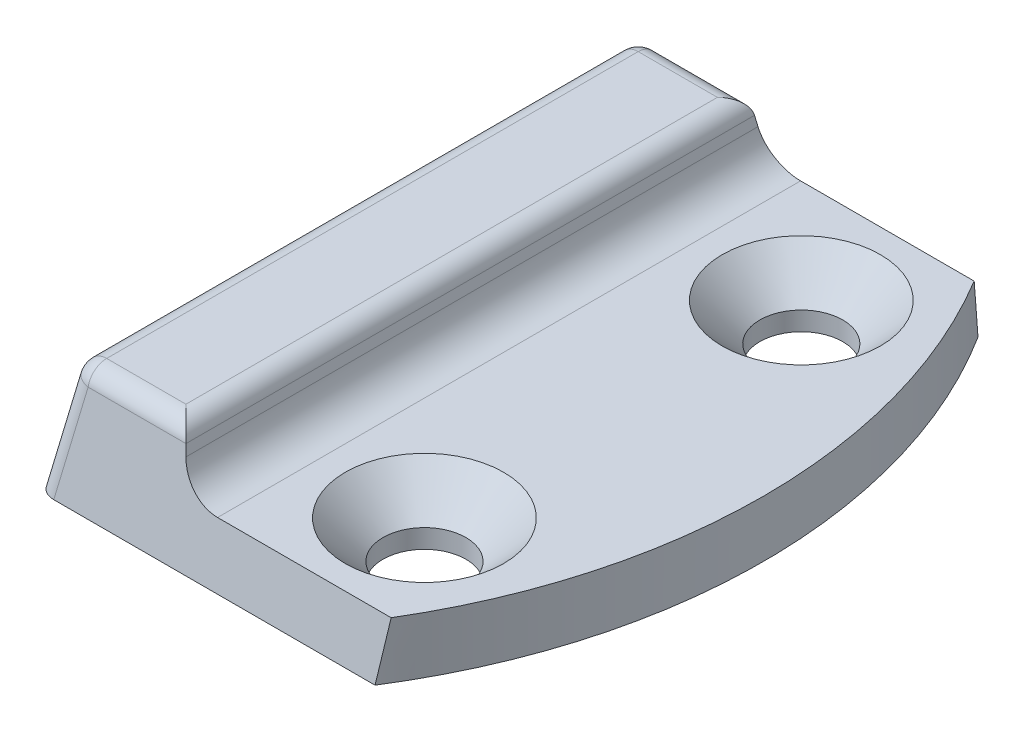
SolidWorks part; units mm, degrees
ref_plane "Спереди" through (0, 0, 0) normal (0, 0, 1) x (1, 0, 0)
ref_plane "Сверху" through (0, 0, 0) normal (0, 1, 0) x (1, 0, 0)
ref_plane "Справа" through (0, 0, 0) normal (1, 0, 0) x (0, 0, -1)
sketch "Эскиз1" plane through (0, 0, 0) normal (0, 1, 0) x (1, 0, 0)
  line L0 (0, 33.2845) -> (0, -21.3972) construction
  line L1 (0, 0) -> (27.1923, 0) construction
  line L3 (3.671, 8) -> (7.671, 8)
  line L4 (3.671, 8) -> (3.671, -8)
  line L5 (3.671, -8) -> (7.671, -8)
  line L6 (7.671, 8) -> (7.671, -8)
  line L7 (3.671, 8) -> (7.671, -8) construction
  line L8 (3.671, -8) -> (7.671, 8) construction
  point P4 (5.671, 0)
  dimension "D1" = 3.671
  dimension "D2" = 4
  dimension "D3" = 16
extrude "Бобышка-Вытянуть1" add sketch "Эскиз1" along normal blind 3 draft 10
sketch "Эскиз2" plane through (0, 0, 0) normal (0, 1, 0) x (1, 0, 0)
  line L0 (7.671, 8) -> (12.6886, 8)
  line L1 (7.671, -8) -> (12.6886, -8)
  line L2 (7.671, 8) -> (7.671, -8)
  arc A0 (12.6886, -8) -> (12.6886, 8) centre (0, 0) ccw
  dimension "D1" = 30
extrude "Бобышка-Вытянуть3" add sketch "Эскиз2" along normal blind 1.5 separate body
sketch "Эскиз3" plane through (0, 0, 8) normal (0, 0, 1) x (1, 0, 0)
  line L0 (7.671, 1.5) -> (7.4065, 1.5)
  line L1 (7.142, 3) -> (7.671, 0) construction
  line L2 (7.4065, 1.5) -> (7.671, 0)
  line L3 (7.671, 0) -> (7.671, 1.5)
extrude "Бобышка-Вытянуть4" add sketch "Эскиз3" against normal up to surface (16 mm away) up to face at (10.1798, 0.75, -8)
sketch "Эскиз5" plane through (0, 0, 0) normal (1, 0, 0) x (0, 0, -1)
  line L0 (-8, 0) -> (-8, 1.5)
  line L1 (-8, 1.5) -> (-7.7355, 1.5)
  line L2 (-7.7355, 1.5) -> (-8, 0)
  line L3 (7.7355, 1.5) -> (8, 0)
  line L4 (8, 0) -> (8, 1.5)
  line L5 (8, 1.5) -> (7.7355, 1.5)
extrude "Вырез-Вытянуть1" cut sketch "Эскиз5" along normal up to vertex
sketch "Эскиз6" plane through (0, 1.5, 0) normal (0, 1, 0) x (1, 0, 0)
  line L1 (-11, 5) -> (11, 5) construction
  line L2 (-11, 5) -> (-11, -5) construction
  line L3 (-11, -5) -> (11, -5) construction
  line L4 (11, 5) -> (11, -5) construction
  line L5 (-11, 5) -> (11, -5) construction
  line L6 (-11, -5) -> (11, 5) construction
  circle A0 centre (11, 5) radius 1.1
  circle A1 centre (11, -5) radius 1.1
  point P0 (0, 0)
  dimension "D3" = 2.2
  dimension "D4" = 2.2
  dimension "D1" = 22
  dimension "D2" = 10
extrude "Вырез-Вытянуть2" cut sketch "Эскиз6" against normal through all
chamfer "Фаска1" distance 1 angle 45 2 edges at (9.9, 1.5, 5) (9.9, 1.5, -5)
fillet "Скругление2" radius 1 1 edges at (7.4065, 1.5, 0)
fillet "Скругление3" radius 0.5 6 edges at (7.142, 3, 0) (5.671, 3, 7.471) (3.9355, 1.5, 7.7355) (3.9355, 1.5, -7.7355) (4.2, 3, 0) (5.671, 3, -7.471)
equation "\"motor_D\"= 30'Motor diameter"
equation "\"motor_H\"= 13'Motor heigh"
equation "\"motor_d1\"= 25.4558'Seating diameter of screws on the fixed part of the motor"
equation "\"motor_s1\"= 2'Screws diameter on the fixed part of motor"
equation "\"motor_d2\"= 0'Seating diameter of screws on the moving part of the motor (if this parameter is not determine, write 0)"
equation "\"motor_a2\"= 10'Seating parameter in rectangle of screws on the moving part of the motor"
equation "\"motor_b2\"= 22'Seating parameter in rectangle of screws on the moving part of the motor"
equation "\"motor_s2\"= 2'Screws diameter on the moving part of motor"
equation "\"motor_cmd\"= 12'Central magnet mount diameter"
equation "\"motor_cmh\"= 1.4'Central magnet mount heigh (if not write 0)"
equation "\"motor_Dc\"= 5'Central hole diameter of motor"
equation "\"motor_whR\"= 10'Distance from center of motor to wires"
equation "\"bearing_d1\"= 6'Bearing inner diameter"
equation "\"bearing_d2\"= 17'Bearing external diameter"
equation "\"bearing h\"= 6'Bearing heigh"
equation "\"pin_d\"= 2'Pin diameter"
equation "\"pin_h\"= 12'Pin heigh"
equation "\"magnet_d1\"= 5'Magnet inner diameter"
equation "\"magnet_d2\"= 9.5'Magnet external diameter"
equation "\"magnet_h\"= 3'Magnet heigh"
equation "\"print_offset\"= 0.2'Offset for printing holes"
equation "\"ft_sensor_d1\"= 9.8"
equation "\"ft_sensor_d2\"= 24.9"
equation "\"ft_sensor_d3\"= 22.6'Inner diameter of "
equation "\"ft_sensor_h\"= 7.1"
equation "\"ft_sensor_whD\" = 5"
equation "\"D1@Эскиз1\"=(\"pin_d\"+6-(\"pin_d\"+1)*tan(10)*2)/2+0.2"
equation "\"D3@Эскиз1\"=if(\"motor_d2\"=0,if( \"motor_a2\">\"motor_b2\",\"motor_b2\",\"motor_a2\"),\"motor_d2\"*1.5)+\"motor_s2\"*3"
equation "\"D1@Бобышка-Вытянуть1\"=\"pin_d\"+1"
equation "\"D1@Эскиз2\"=\"motor_D\""
equation "\"D1@Эскиз6\"=if( \"motor_d2\"=0,if(\"motor_a2\">\"motor_b2\",\"motor_a2\",\"motor_b2\"),\"motor_d2\"*1.41421356)"
equation "\"D2@Эскиз6\"=if( \"motor_d2\"=0,if(\"motor_a2\">\"motor_b2\",\"motor_b2\",\"motor_a2\"),\"motor_d2\"*1.41421356)"
equation "\"D3@Эскиз6\"=\"motor_s2\"+\"print_offset\""
equation "\"D4@Эскиз6\"=\"D3@Эскиз6\""
